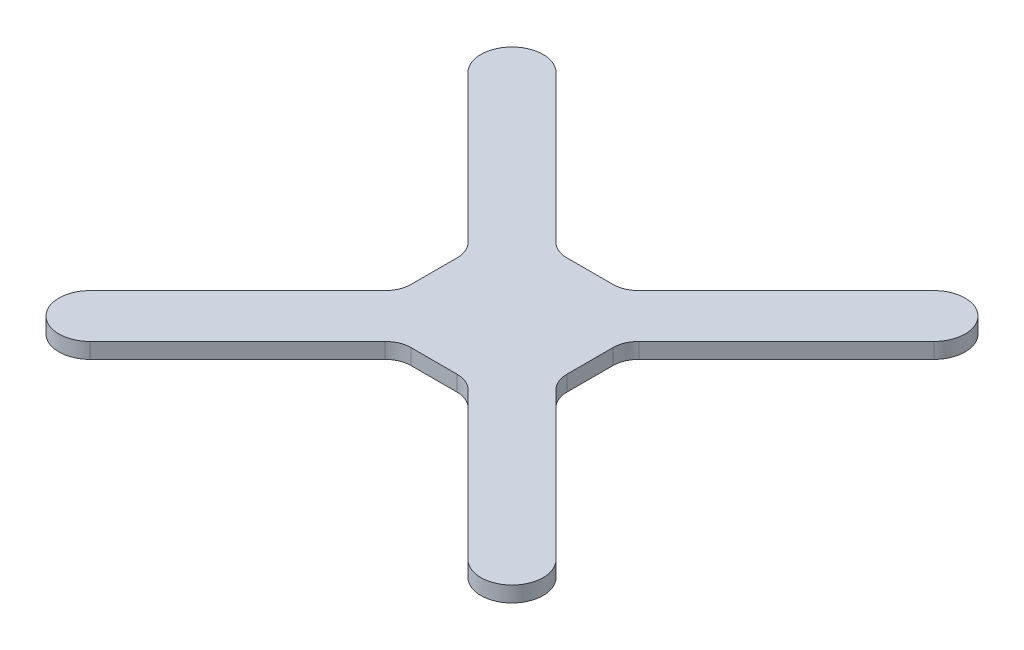
SolidWorks part; units mm, degrees
ref_plane "Front Plane" through (0, 0, 0) normal (0, 0, 1) x (1, 0, 0)
ref_plane "Top Plane" through (0, 0, 0) normal (0, 1, 0) x (1, 0, 0)
ref_plane "Right Plane" through (0, 0, 0) normal (1, 0, 0) x (0, 0, -1)
sketch "Sketch1" plane through (0, 0, 0) normal (0, 1, 0) x (1, 0, 0)
  line L0 (-81.3173, 81.3173) -> (81.3173, -81.3173) construction
  line L1 (-98.425, -98.425) -> (98.425, -98.425) construction
  line L2 (-98.425, -98.425) -> (-98.425, 98.425) construction
  line L3 (-98.425, 98.425) -> (98.425, 98.425) construction
  line L4 (98.425, -98.425) -> (98.425, 98.425) construction
  line L5 (-98.425, -98.425) -> (98.425, 98.425) construction
  line L6 (-98.425, 98.425) -> (98.425, -98.425) construction
  line L7 (-72.832, 89.8026) -> (-13.0294, 30)
  line L8 (-89.8026, 72.832) -> (-30, 13.0294)
  line L9 (0, 98.425) -> (0, -98.425) construction
  line L10 (81.3173, 81.3173) -> (-81.3173, -81.3173) construction
  line L11 (72.832, 89.8026) -> (13.0294, 30)
  line L12 (89.8026, 72.832) -> (30, 13.0294)
  line L13 (-30, -13.0294) -> (-89.8026, -72.832)
  line L14 (-13.0294, -30) -> (13.0294, -30)
  line L15 (-30, -13.0294) -> (-30, 13.0294)
  line L16 (-13.0294, 30) -> (13.0294, 30)
  line L17 (30, -13.0294) -> (30, 13.0294)
  line L18 (-30, -30) -> (30, 30) construction
  line L19 (-30, 30) -> (30, -30) construction
  line L20 (-13.0294, -30) -> (-72.832, -89.8026)
  line L21 (30, -13.0294) -> (89.8026, -72.832)
  line L22 (13.0294, -30) -> (72.832, -89.8026)
  arc A0 (-72.832, 89.8026) -> (-89.8026, 72.832) centre (-81.3173, 81.3173) ccw
  arc A1 (72.832, -89.8026) -> (89.8026, -72.832) centre (81.3173, -81.3173) ccw
  circle A2 centre (-81.3173, 81.3173) radius 8 construction
  circle A3 centre (81.3173, -81.3173) radius 8 construction
  circle A4 centre (-81.3173, -81.3173) radius 8 construction
  circle A5 centre (81.3173, 81.3173) radius 8 construction
  arc A6 (72.832, 89.8026) -> (89.8026, 72.832) centre (81.3173, 81.3173) cw
  arc A7 (-72.832, -89.8026) -> (-89.8026, -72.832) centre (-81.3173, -81.3173) cw
  point P0 (0, 0)
  point P8 (0, 0)
  point P23 (0, 0)
  point P28 (0, 0)
  point P29 (0, 0)
  point P42 (30, 0)
  point P43 (0, 0)
  dimension "D2" = 12
  dimension "D4" = 16
  dimension "D6" = 12
  dimension "D9" = 12
  dimension "D10" = 12
  dimension "D1" = 196.85
  dimension "D3" = 115
  dimension "D5" = 115
  dimension "D7" = 60
  dimension "D8" = 26.0589
  dimension "D11" = 30
  dimension "D12" = 30
extrude "Boss-Extrude1" add sketch "Sketch1" along normal blind 6
fillet "Fillet1" radius 10 8 edges at (-30, 3, -13.0294) (-30, 3, 13.0294) (-13.0294, 3, -30) (13.0294, 3, -30) (30, 3, 13.0294) (30, 3, -13.0294) (13.0294, 3, 30) (-13.0294, 3, 30)
